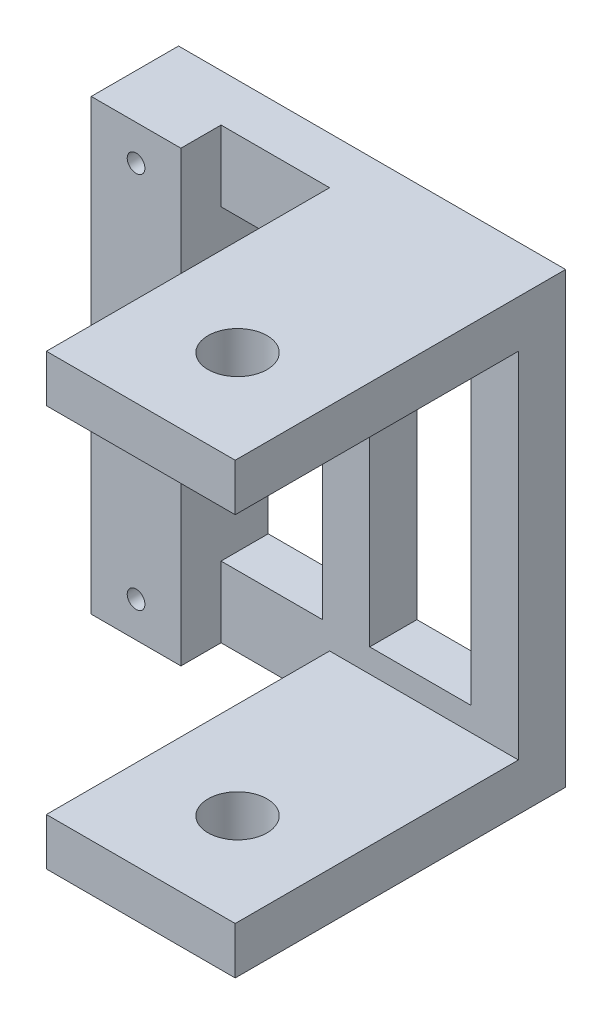
SolidWorks part; units mm, degrees
ref_plane "前视基准面" through (0, 0, 0) normal (0, 0, 1) x (1, 0, 0)
ref_plane "上视基准面" through (0, 0, 0) normal (0, 1, 0) x (1, 0, 0)
ref_plane "右视基准面" through (0, 0, 0) normal (1, 0, 0) x (0, 0, -1)
sketch "草图2" plane through (0, 0, 0) normal (0, 0, 1) x (1, 0, 0)
  line L3 (-9.1, -9.5) -> (7.3, -9.5)
  line L4 (7.3, 9.5) -> (7.3, -9.5)
  line L5 (0, 0) -> (2.4933, 0) construction
  line L6 (0, 0) -> (0, -3.9686) construction
  line L15 (-9.1, 9.5) -> (7.3, 9.5)
  line L16 (-5.3, 6.5) -> (-1, 6.5)
  line L17 (-5.3, 6.5) -> (-5.3, -6.5)
  line L18 (-5.3, -6.5) -> (-1, -6.5)
  line L20 (-9.1, 9.5) -> (-9.1, -9.5)
  line L21 (1, 6.5) -> (5.3, 6.5)
  line L23 (1, -6.5) -> (1, 6.5)
  line L25 (-1, -6.5) -> (-1, 6.5)
  line L26 (5.3, 6.5) -> (5.3, -6.5)
  line L28 (1, -6.5) -> (5.3, -6.5)
  point P0 (0, 0)
  dimension "D1" = 16.4
  dimension "D3" = 19
  dimension "D4" = 3.8
  dimension "D5" = 3
  dimension "D6" = 2
  dimension "D8" = 3
  dimension "D9" = 2
extrude "凸台-拉伸1" add sketch "草图2" along normal blind 2
sketch "草图3" plane through (0, 0, 2) normal (0, 0, 1) x (1, 0, 0)
  line L1 (-0.7, 9.5) -> (7.3, 9.5)
  line L2 (-0.7, 9.5) -> (-0.7, 7.5)
  line L3 (-0.7, 7.5) -> (7.3, 7.5)
  line L4 (7.3, 9.5) -> (7.3, 7.5)
  line L5 (7.3, -9.5) -> (7.3, 9.5) construction
  line L6 (-0.7, -7.5) -> (7.3, -7.5)
  line L8 (-0.7, -9.5) -> (7.3, -9.5)
  line L9 (7.3, -7.5) -> (7.3, -9.5)
  line L10 (-9.1, -9.5) -> (7.3, -9.5) construction
  line L11 (-0.7, -7.5) -> (-0.7, -9.5)
  line L12 (7.3, 9.5) -> (-9.1, 9.5) construction
  dimension "D1" = 2
  dimension "D2" = 2
  dimension "D3" = 8
  dimension "D4" = 8
extrude "凸台-拉伸2" add sketch "草图3" along normal blind 12
sketch "草图10" plane through (0, 0, 2) normal (0, 0, 1) x (1, 0, 0)
  line L0 (-9.1, 9.5) -> (-9.1, -9.5) construction
  line L1 (-9.1, 9.5) -> (-5.3, 9.5)
  line L2 (-9.1, 9.5) -> (-9.1, -9.5)
  line L3 (-9.1, -9.5) -> (-5.3, -9.5)
  line L4 (-5.3, 9.5) -> (-5.3, -9.5)
  line L5 (-0.7, 9.5) -> (-9.1, 9.5) construction
  line L6 (-9.1, -9.5) -> (-0.7, -9.5) construction
  line L7 (-5.3, 6.5) -> (-5.3, -6.5) construction
extrude "凸台-拉伸4" add sketch "草图10" along normal blind 1.7
sketch "草图9" plane through (0, 0, 2) normal (0, 0, 1) x (1, 0, 0)
  line L0 (-0.7, 9.5) -> (-5.3, 9.5) construction
  line L1 (-9.1, 9.5) -> (-9.1, -9.5) construction
  line L2 (-5.3, -9.5) -> (-0.7, -9.5) construction
  circle A0 centre (-7.2, 8) radius 0.375
  circle A1 centre (-7.2, -8) radius 0.375
  dimension "D1" = 0.75
  dimension "D2" = 0.75
  dimension "D3" = 1.5
  dimension "D4" = 1.9
  dimension "D5" = 1.5
  dimension "D6" = 1.9
extrude "切除-拉伸2" cut sketch "草图9" against normal up to next (2 mm away) from surface at 1.7 starting at face at (-7.2, 0, 3.7)
sketch "草图11" plane through (0, -9.5, 0) normal (0, -1, 0) x (1, 0, 0)
  circle A0 centre (3.4, 10) radius 1.25
  dimension "D1" = 2.5
extrude "切除-拉伸3" cut sketch "草图11" against normal through all
